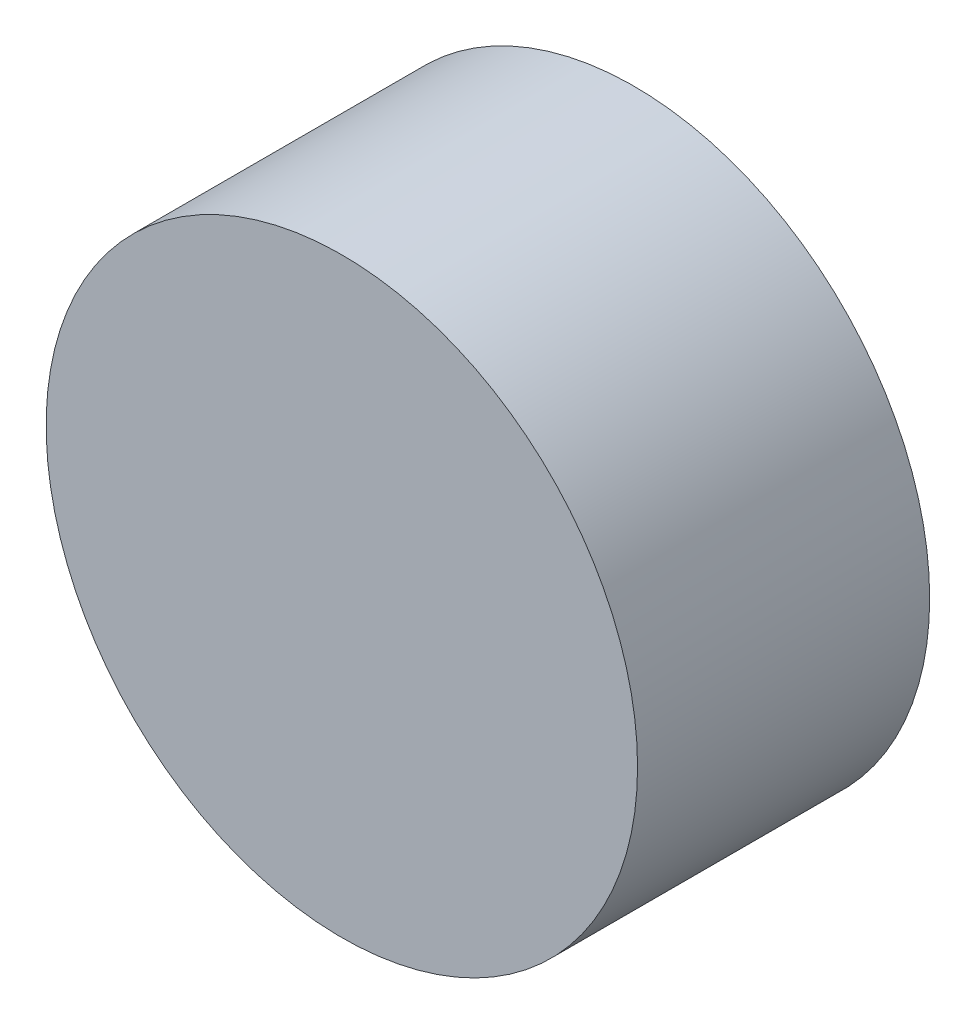
SolidWorks part; units mm, degrees
ref_plane "Front Plane" through (0, 0, 0) normal (0, 0, 1) x (1, 0, 0)
ref_plane "Top Plane" through (0, 0, 0) normal (0, 1, 0) x (1, 0, 0)
ref_plane "Right Plane" through (0, 0, 0) normal (1, 0, 0) x (0, 0, -1)
sketch "Sketch1" plane through (0, 0, 0) normal (0, 1, 0) x (1, 0, 0)
  line L0 (10.1235, 0) -> (0, 0)
  line L1 (0, 0) -> (0, -10)
  line L2 (0, -10) -> (10.1235, -10)
  line L3 (10.1235, -10) -> (10.1235, 0)
  line L4 (0, 0) -> (0, -10) construction
revolve "Revolve1" add sketch "Sketch1" angle 360 about L4
